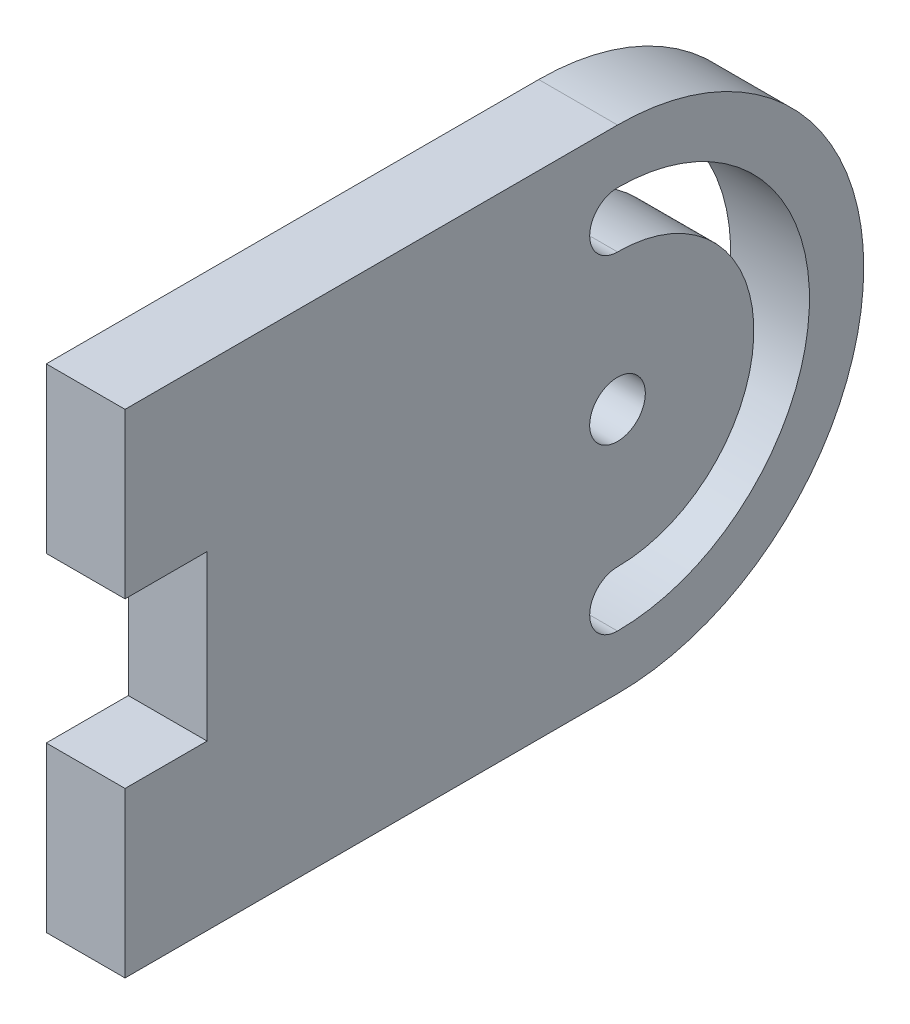
SolidWorks part; units mm, degrees
ref_plane "Front Plane" through (0, 0, 0) normal (0, 0, 1) x (1, 0, 0)
ref_plane "Top Plane" through (0, 0, 0) normal (0, 1, 0) x (1, 0, 0)
ref_plane "Right Plane" through (0, 0, 0) normal (1, 0, 0) x (0, 0, -1)
sketch "Sketch1" plane through (0, 0, 0) normal (1, 0, 0) x (0, 0, -1)
  line L0 (0, 6.35) -> (0, -6.35)
  line L1 (0, -6.35) -> (-6.35, -6.35)
  line L2 (-6.35, -6.35) -> (-6.35, -19.05)
  line L3 (0, 6.35) -> (-6.35, 6.35)
  line L4 (-6.35, 6.35) -> (-6.35, 19.05)
  line L5 (-6.35, 19.05) -> (31.75, 19.05)
  line L6 (-6.35, -19.05) -> (31.75, -19.05)
  arc A0 (31.75, 19.05) -> (31.75, -19.05) centre (31.75, 0) cw
  point P3 (0, 0)
  dimension "D1" = 6.35
  dimension "D2" = 12.7
  dimension "D3" = 38.1
extrude "Boss-Extrude1" add sketch "Sketch1" along normal mid plane 6.096
hole_wizard "#8 Clearance Hole1" positions "Sketch3" profile "Sketch4" hole size "#8" standard "ANSI Inch" end condition through all
sketch "Sketch3" plane through (3.048, 0, 0) normal (1, 0, 0) x (0, 0, -1)
  line L0 (12.954, 0) -> (-49987.046, 0) construction
  point P0 (31.75, 0)
  point P3 (31.75, 12.7)
  point P5 (31.75, -12.7)
  dimension "D1" = 25.4
sketch "Sketch4" plane through (3.048, 0, -31.75) normal (0, 1, 0) x (0, 0, -1)
  line L0 (0, 0) -> (0, 6.096)
  line L1 (0, 6.096) -> (2.1526, 6.096)
  line L2 (2.1526, 6.096) -> (2.1526, 0)
  line L5 (2.1526, 0) -> (0, 0)
  line L11 (0, -6.35) -> (0, 107.95) construction
  dimension "Thru Hole Dia." = 4.3053
  dimension "Thru Hole Depth" = 6.096
sketch "Sketch5" plane through (3.048, 0, 0) normal (1, 0, 0) x (0, 0, -1)
  arc A0 (31.75, 10.5474) -> (31.75, -10.5474) centre (31.75, 0) cw
  circle A1 centre (31.75, 12.7) radius 2.1526 construction
  circle A2 centre (31.75, -12.7) radius 2.1526 construction
  arc A3 (31.75, 14.8526) -> (31.75, -14.8526) centre (31.75, 0) cw
  circle A4 centre (31.75, -12.7) radius 2.1526
  circle A5 centre (31.75, 12.7) radius 2.1526
  circle M2 centre (31.75, 12.7) radius 2.1526
  circle M3 centre (31.75, -12.7) radius 2.1526
extrude "Cut-Extrude1" cut sketch "Sketch5" against normal through all contours A3 A0 M2 M3
